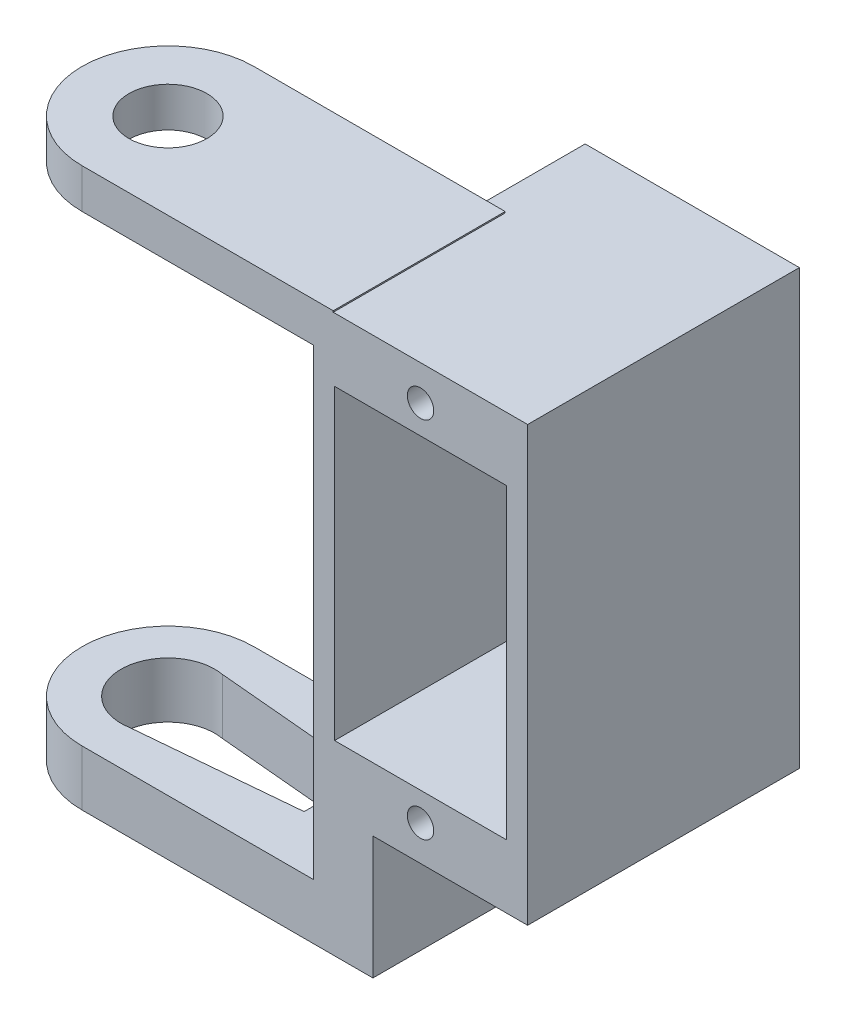
SolidWorks part; units mm, degrees
material "ABS"
ref_plane "Front Plane" through (0, 0, 0) normal (0, 0, 1) x (1, 0, 0)
ref_plane "Top Plane" through (0, 0, 0) normal (0, 1, 0) x (1, 0, 0)
ref_plane "Right Plane" through (0, 0, 0) normal (1, 0, 0) x (0, 0, -1)
sketch "Sketch1" plane through (0, 0, 0) normal (0, 0, 1) x (1, 0, 0)
  line L1 (-67.5, -75.4) -> (-51.3, -75.4)
  line L2 (-67.5, -75.4) -> (-67.5, -42.6)
  line L3 (-67.5, -42.6) -> (-51.3, -42.6)
  line L4 (-51.3, -75.4) -> (-51.3, -42.6)
extrude "Boss-Extrude1" add sketch "Sketch1" along normal mid plane 20.55 from offset 3.775
sketch "Sketch2" plane through (0, 0, 0) normal (1, 0, 0) x (0, 0, -1)
  line L1 (-6.5, -84.7) -> (6.5, -84.7)
  line L2 (-6.5, -84.7) -> (-6.5, -73)
  line L3 (-6.5, -73) -> (6.5, -73)
  line L4 (6.5, -84.7) -> (6.5, -73)
extrude "Boss-Extrude2" add sketch "Sketch2" along normal mid plane 4.5 from offset 65.25
sketch "Sketch3" plane through (0, 0, 0) normal (0, 1, 0) x (1, 0, 0)
  circle A0 centre (-85, 0) radius 6.5
extrude "Boss-Extrude3" add sketch "Sketch3" along normal mid plane 4.2 from offset 82.6
sketch "Sketch4" plane through (0, 0, 0) normal (0, 1, 0) x (1, 0, 0)
  line L1 (-85, -6.5) -> (-66, -6.5)
  line L2 (-85, -6.5) -> (-85, 6.5)
  line L3 (-85, 6.5) -> (-66, 6.5)
  line L4 (-66, -6.5) -> (-66, 6.5)
  circle A0 centre (-85, 0) radius 6.5 construction
extrude "Boss-Extrude4" add sketch "Sketch4" along normal mid plane 4.2 from offset 82.6
sketch "Sketch5" plane through (0, 0, 0) normal (0, 1, 0) x (1, 0, 0)
  circle A0 centre (-85, 0) radius 3.55
extrude "Cut-Extrude1" cut sketch "Sketch5" against normal mid plane 4.2 from offset 82.6
sketch "Sketch6" plane through (0, 0, 0) normal (0, 1, 0) x (1, 0, 0)
  line L0 (-85, -3.55) -> (-72.3, -2.4033)
  line L1 (-72.3, -2.4033) -> (-72.3, 2.4033)
  line L2 (-72.3, 2.4033) -> (-85, 3.55)
  line L3 (-85, 3.55) -> (-85, -3.55)
  circle A0 centre (-85, 0) radius 3.55 construction
extrude "Cut-Extrude2" cut sketch "Sketch6" against normal mid plane 4.2 from offset 82.6
sketch "Sketch7" plane through (0, 0, 0) normal (0, 1, 0) x (1, 0, 0)
  circle A0 centre (-85, 0) radius 6.5
extrude "Boss-Extrude5" add sketch "Sketch7" along normal mid plane 3 from offset 44
sketch "Sketch8" plane through (0, 0, 0) normal (0, 1, 0) x (1, 0, 0)
  line L1 (-85, -6.5) -> (-66, -6.5)
  line L2 (-85, -6.5) -> (-85, 6.5)
  line L3 (-85, 6.5) -> (-66, 6.5)
  line L4 (-66, -6.5) -> (-66, 6.5)
  circle A0 centre (-85, 0) radius 6.5 construction
extrude "Boss-Extrude6" add sketch "Sketch8" along normal mid plane 3 from offset 44
sketch "Sketch9" plane through (0, 0, 0) normal (0, 1, 0) x (1, 0, 0)
  circle A0 centre (-85, 0) radius 2.95
extrude "Cut-Extrude3" cut sketch "Sketch9" against normal mid plane 3 from offset 44
sketch "Sketch10" plane through (0, 0, 0) normal (0, 0, 1) x (1, 0, 0)
  line L1 (-65.9, -70.6) -> (-52.9, -70.6)
  line L2 (-65.9, -70.6) -> (-65.9, -47.4)
  line L3 (-65.9, -47.4) -> (-52.9, -47.4)
  line L4 (-52.9, -70.6) -> (-52.9, -47.4)
extrude "Cut-Extrude4" cut sketch "Sketch10" against normal mid plane 17.25 from offset 2.125
sketch "Sketch11" plane through (0, 0, 0) normal (0, 0, 1) x (1, 0, 0)
  circle A0 centre (-59.4, -45.25) radius 1
extrude "Cut-Extrude5" cut sketch "Sketch11" against normal mid plane 6 from offset 3.5
sketch "Sketch12" plane through (0, 0, 0) normal (0, 0, 1) x (1, 0, 0)
  circle A0 centre (-59.4, -72.75) radius 1
extrude "Cut-Extrude6" cut sketch "Sketch12" against normal mid plane 6 from offset 3.5
sketch "Sketch13" plane through (0, 0, 0) normal (0, 0, 1) x (1, 0, 0)
  circle A0 centre (-59.4, -64.5) radius 3.15
extrude "Cut-Extrude7" cut sketch "Sketch13" against normal mid plane 2.6 from offset 12.75
sketch "Sketch14" plane through (0, 0, 0) normal (0, 1, 0) x (1, 0, 0)
  line L1 (-61.6, 4.75) -> (-57.2, 4.75)
  line L2 (-61.6, 4.75) -> (-61.6, 10.75)
  line L3 (-61.6, 10.75) -> (-57.2, 10.75)
  line L4 (-57.2, 4.75) -> (-57.2, 10.75)
extrude "Cut-Extrude8" cut sketch "Sketch14" against normal mid plane 4.8 from offset 73
